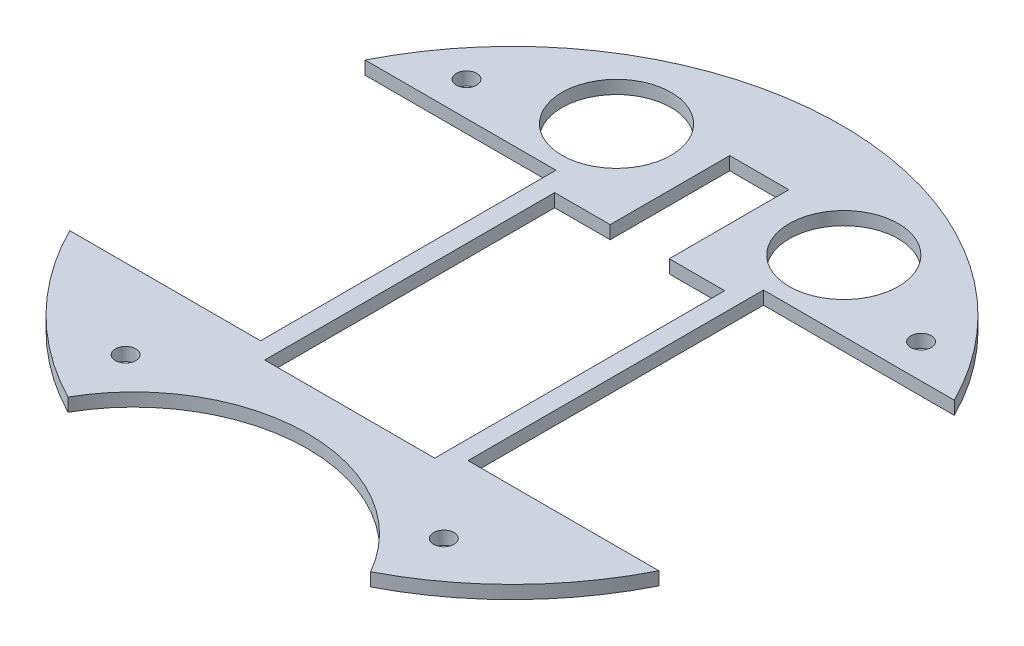
SolidWorks part; units mm, degrees
material "Acrylic (Medium-high impact)"
ref_plane "Front Plane" through (0, 0, 0) normal (0, 0, 1) x (1, 0, 0)
ref_plane "Top Plane" through (0, 0, 0) normal (0, 1, 0) x (1, 0, 0)
ref_plane "Right Plane" through (0, 0, 0) normal (1, 0, 0) x (0, 0, -1)
sketch "Sketch1" plane through (0, 0, 0) normal (0, 1, 0) x (1, 0, 0)
  line L0 (0, -83.2398) -> (-33.2911, -64.4046) construction
  line L1 (0, -83.2398) -> (0, 0) construction
  arc A0 (33.2911, -64.4046) -> (-33.2911, -64.4046) centre (0, 0) ccw
  arc A1 (33.2911, -64.4046) -> (-33.2911, -64.4046) centre (0, -83.2398) ccw
  dimension "D1" = 145
  dimension "D2" = 76.5
  dimension "D3" = 60.5
extrude "Boss-Extrude1" add sketch "Sketch1" along normal blind 2.9
sketch "solenoid placement" plane through (0, 2.9, 0) normal (0, 1, 0) x (1, 0, 0)
  line L4 (-18.7, -35.7) -> (18.7, -35.7)
  line L5 (18.7, -35.7) -> (18.7, 28.1)
  line L6 (18.7, 28.1) -> (-18.7, 28.1)
  line L7 (-18.7, 28.1) -> (-18.7, -35.7)
  line L8 (-18.7, -35.7) -> (18.7, -35.7)
  line L9 (18.7, -35.7) -> (18.7, 28.1)
  line L10 (18.7, 28.1) -> (-18.7, 28.1)
  line L11 (-18.7, 28.1) -> (-18.7, -35.7)
  circle A1 centre (0, 0) radius 72.5 construction
  arc A2 (33.2911, -64.4046) -> (-33.2911, -64.4046) centre (0, 0) ccw construction
  dimension "D1" = 0
extrude "Cut-Extrude1" cut sketch "solenoid placement" against normal through all
sketch "Sketch3" plane through (0, 2.9, 0) normal (0, 1, 0) x (1, 0, 0)
  line L4 (-34.63, -32.5) -> (-22.83, -32.5)
  line L5 (-22.83, -32.5) -> (-22.83, 32.5)
  line L6 (-22.83, 32.5) -> (-64.8074, 32.5)
  line L7 (-64.8074, -32.5) -> (-34.63, -32.5)
  line L8 (-34.63, -32.5) -> (-22.83, -32.5)
  line L9 (-22.83, -32.5) -> (-22.83, 32.5)
  line L10 (-22.83, 32.5) -> (-64.8074, 32.5)
  line L11 (-64.8074, -32.5) -> (-34.63, -32.5)
  line L12 (34.63, -32.5) -> (64.8074, -32.5)
  line L13 (64.8074, 32.5) -> (22.83, 32.5)
  line L14 (22.83, 32.5) -> (22.83, -32.5)
  line L15 (22.83, -32.5) -> (34.63, -32.5)
  line L16 (34.63, -32.5) -> (64.8074, -32.5)
  line L17 (64.8074, 32.5) -> (22.83, 32.5)
  line L18 (22.83, 32.5) -> (22.83, -32.5)
  line L19 (22.83, -32.5) -> (34.63, -32.5)
  arc A2 (-64.8074, 32.5) -> (-64.8074, -32.5) centre (0, 0) ccw
  arc A3 (-64.8074, 32.5) -> (-64.8074, -32.5) centre (0, 0) ccw
  arc A4 (64.8074, -32.5) -> (64.8074, 32.5) centre (0, 0) ccw
  arc A5 (64.8074, -32.5) -> (64.8074, 32.5) centre (0, 0) ccw
  dimension "D2" = 0
  dimension "D1" = 0
extrude "Cut-Extrude3" cut sketch "Sketch3" against normal through all
sketch "Sketch4" plane through (0, 2.9, 0) normal (0, 1, 0) x (1, 0, 0)
  line L0 (18.7, 28.1) -> (-18.7, 28.1) construction
  line L1 (-6.5, 28.1) -> (6.5, 28.1)
  line L2 (-6.5, 28.1) -> (-6.5, 54.4)
  line L3 (6.5, 54.4) -> (-6.5, 54.4) construction
  line L4 (6.5, 28.1) -> (6.5, 54.4)
  line L5 (6.5, 54.4) -> (-6.5, 54.4)
  point P6 (0, 28.1)
extrude "Cut-Extrude4" cut sketch "Sketch4" against normal through all
sketch "Sketch5" plane through (0, 2.9, 0) normal (0, 1, 0) x (1, 0, 0)
  circle A2 centre (-25, 48) radius 12
  circle A3 centre (-25, 48) radius 12
  circle A4 centre (25, 48) radius 12
  circle A21 centre (25, 48) radius 12
  dimension "D1" = 0
  dimension "D2" = 0
extrude "Cut-Extrude5" cut sketch "Sketch5" against normal through all
sketch "Sketch6" plane through (0, 2.9, 0) normal (0, 1, 0) x (1, 0, 0)
  circle A1 centre (35, -50) radius 2.25
  circle A2 centre (35, -50) radius 2.25
  circle A3 centre (-35, -50) radius 2.25
  circle A4 centre (-35, -50) radius 2.25
  circle A5 centre (-50, 40) radius 2.25
  circle A6 centre (-50, 40) radius 2.25
  circle A7 centre (50, 40) radius 2.25
  circle A8 centre (50, 40) radius 2.25
  dimension "D1" = 0
  dimension "D2" = 0
  dimension "D3" = 0
  dimension "D4" = 0
extrude "Cut-Extrude6" cut sketch "Sketch6" against normal through all
equation "\"smallPulleyTeeth\"= 15"
equation "\"largePulleyTeeth\"= 30"
equation "\"eighthThick\"= 2.9mm"
equation "\"sixteenthThick\"= 1.7mm"
equation "\"quarterThick\"=5.9mm"
equation "\"OD\"= 145mm"
equation "\"puckAngle\"= 60.5deg"
equation "\"D1@Sketch1\"=\"OD\""
equation "\"puckDiam\"= 76.5mm"
equation "\"D2@Sketch1\"=\"puckDiam\""
equation "\"D3@Sketch1\"=\"puckAngle\""
equation "\"D1@Boss-Extrude1\"=\"eighthThick\""
equation "\"axlePress\"= 5.9mm"
equation "\"press\"= 0.2mm"
equation "\"wheelClear\"= 0.3mm"
equation "\"10-32clear\"= 4.5mm"
equation "\"6-32clear\"= 3.3mm"
equation "\"8-32clear\"= 4.0mm"
equation "\"wheelHeight\"= 22mm"
equation "\"wheelWell\"= 65mm"
